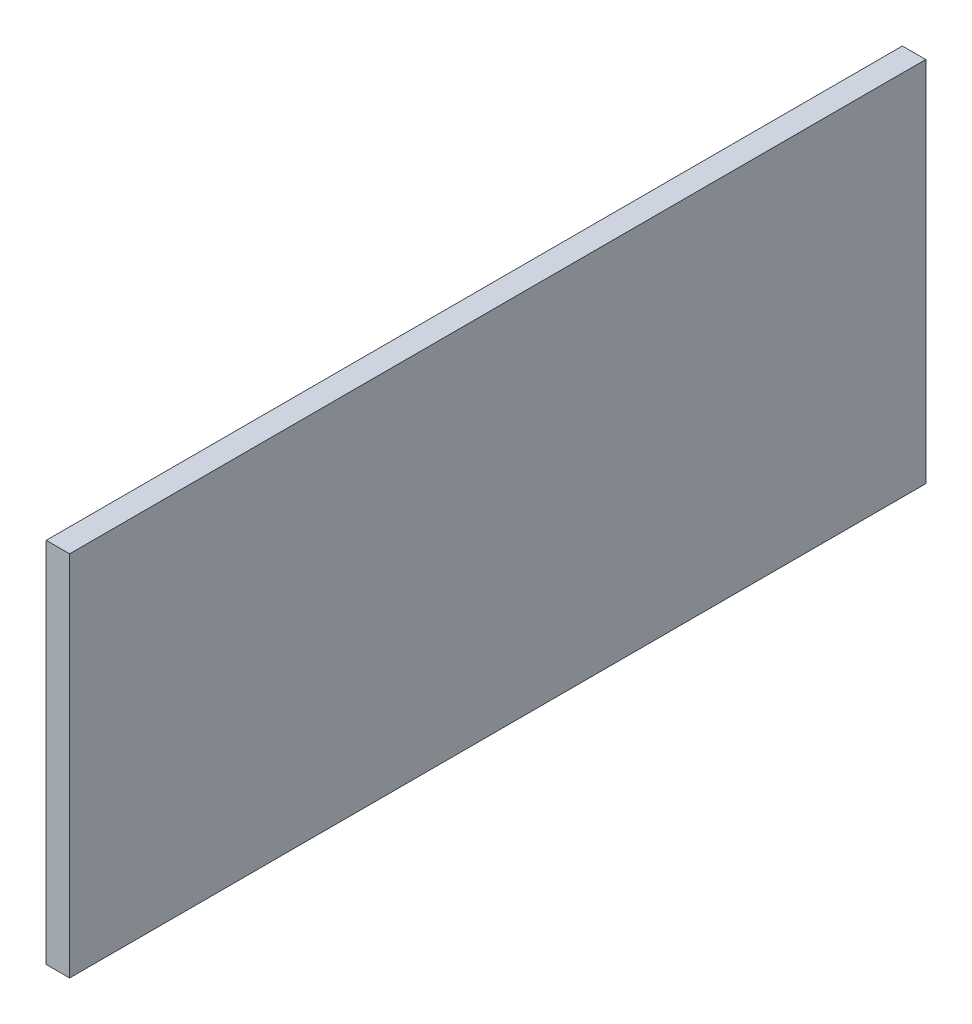
SolidWorks part; units mm, degrees
material "ABS PC"
ref_plane "X-Y Datum" through (0, 0, 0) normal (0, 0, 1) x (1, 0, 0)
ref_plane "X-Z Datum" through (0, 0, 0) normal (0, 1, 0) x (1, 0, 0)
ref_plane "Y-Z Datum" through (0, 0, 0) normal (1, 0, 0) x (0, 0, -1)
sketch "Sketch1" plane through (0, 0, 0) normal (0, 0, 1) x (1, 0, 0)
  line L1 (-3.175, -49.85) -> (3.175, -49.85)
  line L2 (-3.175, -49.85) -> (-3.175, 49.85)
  line L3 (-3.175, 49.85) -> (3.175, 49.85)
  line L4 (3.175, -49.85) -> (3.175, 49.85)
  line L5 (-3.175, -49.85) -> (3.175, 49.85) construction
  line L6 (-3.175, 49.85) -> (3.175, -49.85) construction
  point P0 (0, 0)
  dimension "D1" = 99.7001
  dimension "D2" = 6.35
extrude "Boss-Extrude1" add sketch "Sketch1" along normal blind 232.349
ref_plane "Plane1" through (104.775, -38.0378, 25.4) normal (0, 1, 0) x (1, 0, 0)
